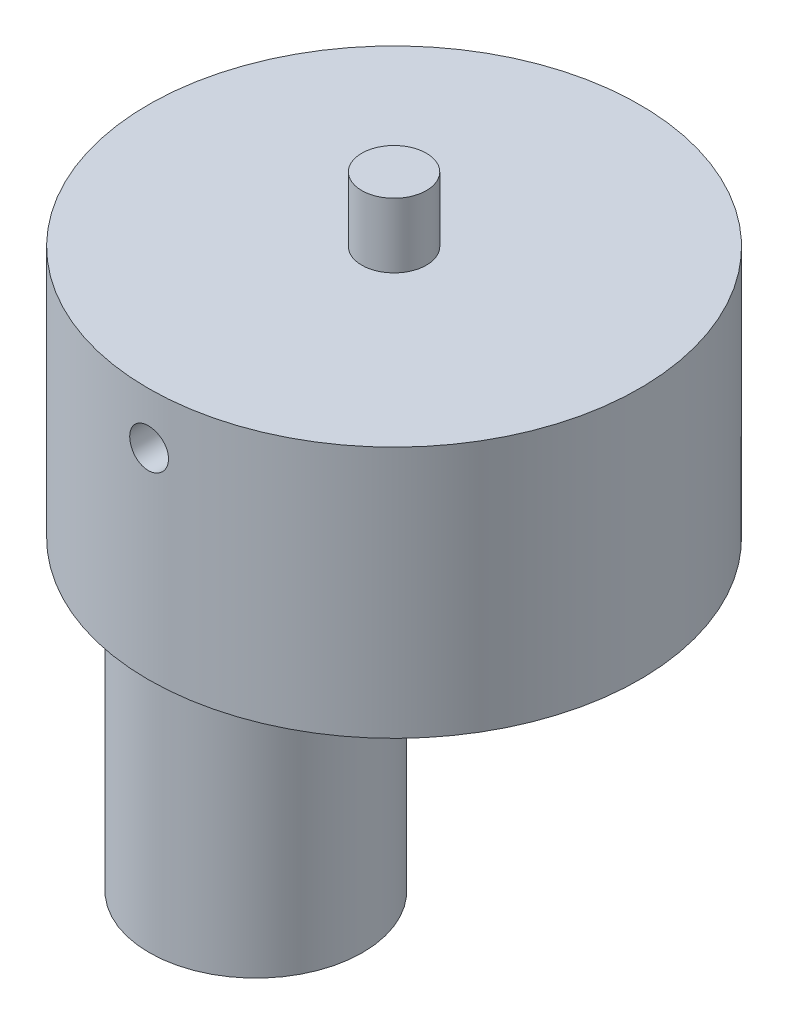
SolidWorks part; units mm, degrees
ref_plane "Спереди" through (0, 0, 0) normal (0, 0, 1) x (1, 0, 0)
ref_plane "Сверху" through (0, 0, 0) normal (0, 1, 0) x (1, 0, 0)
ref_plane "Справа" through (0, 0, 0) normal (1, 0, 0) x (0, 0, -1)
sketch "Эскиз1" plane through (0, 0, 0) normal (0, 1, 0) x (1, 0, 0)
  circle A0 centre (0, 0) radius 38
  dimension "D1" = 76
extrude "Вытянуть1" add sketch "Эскиз1" along normal blind 39
sketch "Эскиз2" plane through (0, 39, 0) normal (0, 1, 0) x (1, 0, 0)
  circle A0 centre (0, 0) radius 5
  dimension "D1" = 10
extrude "Вытянуть2" add sketch "Эскиз2" along normal blind 10
sketch "Эскиз6" plane through (0, 0, 0) normal (0, -1, 0) x (1, 0, 0)
  circle A0 centre (-21.3727, 0) radius 16.5
extrude "Вытянуть6" add sketch "Эскиз6" along normal blind 58
sketch "Sketch1" plane through (0, 0, 0) normal (0, 0, 1) x (1, 0, 0)
  line L0 (-54.642, 31) -> (61.6729, 31) construction
  line L1 (38, 39) -> (-38, 39) construction
  line L2 (0, 39) -> (0, 53.5046) construction
  circle A0 centre (0, 31) radius 3
  dimension "D1" = 8
extrude "Cut-Extrude1" cut sketch "Sketch1" against normal mid plane 100
